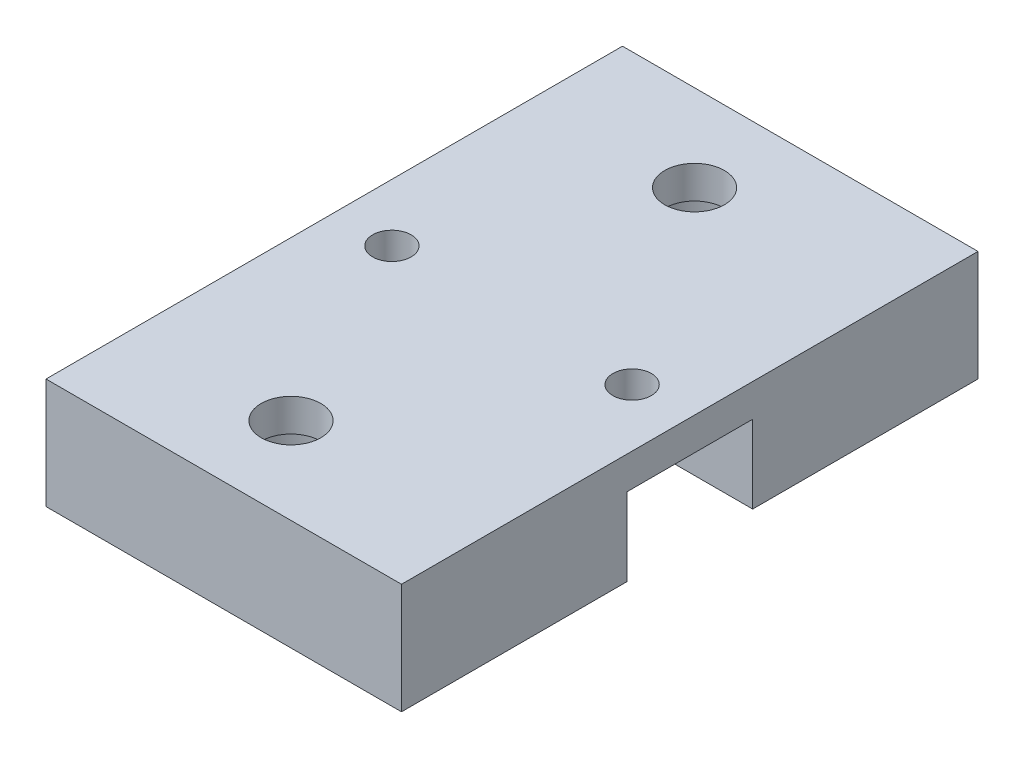
SolidWorks part; units mm, degrees
ref_plane "Front Plane" through (0, 0, 0) normal (0, 0, 1) x (1, 0, 0)
ref_plane "Top Plane" through (0, 0, 0) normal (0, 1, 0) x (1, 0, 0)
ref_plane "Right Plane" through (0, 0, 0) normal (1, 0, 0) x (0, 0, -1)
sketch "Sketch7" plane through (0, 0, 0) normal (0, 1, 0) x (1, 0, 0)
  line L0 (25, 0) -> (62, 0) construction
  line L1 (25, 30) -> (62, 30)
  line L2 (25, 30) -> (25, -30)
  line L3 (25, -30) -> (62, -30)
  line L4 (62, 30) -> (62, -30)
  line L5 (56, 0) -> (31, 0) construction
  circle A0 centre (41.5, 21) radius 3.1
  circle A1 centre (41.5, -21) radius 3.1
  circle A2 centre (56, 0) radius 2
  circle A3 centre (31, 0) radius 2
  point P4 (25, 0)
  dimension "D3" = 6.2
  dimension "D6" = 4
  dimension "D1" = 60
  dimension "D2" = 37
  dimension "D4" = 42
  dimension "D5" = 16.5
  dimension "D7" = 6
  dimension "D8" = 25
  dimension "D10" = 25
  dimension "D9" = 2
extrude "Boss-Extrude10" add sketch "Sketch7" along normal blind 3.4 separate body
sketch "Sketch8" plane through (0, 0, 0) normal (0, -1, 0) x (1, 0, 0)
  line L0 (25, -30) -> (25, 30) construction
  line L1 (25, 30) -> (62, 30)
  line L2 (25, 30) -> (25, 6.55)
  line L3 (25, 6.55) -> (62, 6.55)
  line L4 (62, 30) -> (62, 6.55)
  line L5 (62, 30) -> (62, -30) construction
  line L6 (25, 0) -> (62, 0) construction
  line L7 (25, -6.55) -> (62, -6.55)
  line L8 (62, -30) -> (62, -6.55)
  line L9 (25, -30) -> (62, -30)
  line L10 (25, -30) -> (25, -6.55)
  line L11 (25, 30) -> (62, 30) construction
  circle A0 centre (41.5, 21) radius 5.5
  circle A1 centre (41.5, -21) radius 5.5
  dimension "D1" = 11
  dimension "D2" = 6.55
extrude "Boss-Extrude12" add sketch "Sketch8" along normal blind 8.1
equation "\"D2@Sketch8\"=6.35mm + 0.2mm"
equation "\"D1@Boss-Extrude10\"=1.750000mm+1.65"
